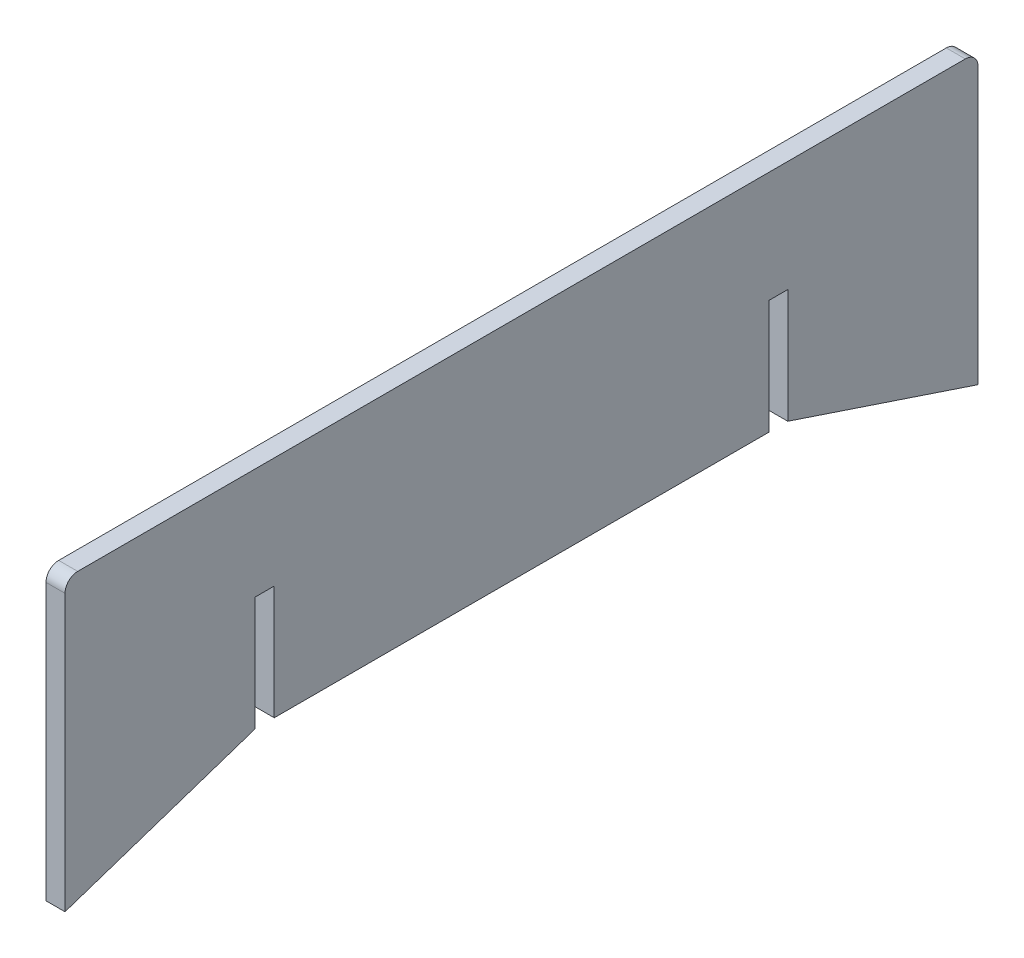
SolidWorks part; units mm, degrees
ref_plane "Front Plane" through (0, 0, 0) normal (0, 0, 1) x (1, 0, 0)
ref_plane "Top Plane" through (0, 0, 0) normal (0, 1, 0) x (1, 0, 0)
ref_plane "Right Plane" through (0, 0, 0) normal (1, 0, 0) x (0, 0, -1)
sketch "Sketch1" plane through (0, 0, 0) normal (1, 0, 0) x (0, 0, -1)
  line L1 (-72, -17.75) -> (72, -17.75)
  line L2 (-72, -17.75) -> (-72, 17.75)
  line L3 (-72, 17.75) -> (72, 17.75)
  line L4 (72, -17.75) -> (72, 17.75)
  line L5 (-72, -17.75) -> (72, 17.75) construction
  line L6 (-72, 17.75) -> (72, -17.75) construction
  point P0 (0, 0)
  dimension "D1" = 35.5
  dimension "D2" = 144
extrude "Boss-Extrude1" add sketch "Sketch1" along normal blind 3
fillet "Fillet1" radius 2 2 edges at (1.5, 17.75, -72) (1.5, 17.75, 72)
sketch "Sketch2" plane through (3, 0, 0) normal (1, 0, 0) x (0, 0, -1)
  line L0 (-72, -17.75) -> (72, -17.75) construction
  line L1 (-42, -17.75) -> (-39, -17.75)
  line L2 (-42, -17.75) -> (-42, 0.25)
  line L3 (-42, 0.25) -> (-39, 0.25)
  line L4 (-39, -17.75) -> (-39, 0.25)
  line L5 (-72, 15.75) -> (-72, -17.75) construction
  line L6 (0, 0) -> (0, -9.6726) construction
  line L7 (42, 0.25) -> (39, 0.25)
  line L8 (39, -17.75) -> (39, 0.25)
  line L9 (42, -17.75) -> (39, -17.75)
  line L10 (42, -17.75) -> (42, 0.25)
  dimension "D1" = 3
  dimension "D2" = 18
  dimension "D3" = 30
extrude "Cut-Extrude1" cut sketch "Sketch2" against normal blind 3
sketch "Sketch3" plane through (3, 0, 0) normal (1, 0, 0) x (0, 0, -1)
  line L0 (-72, -17.75) -> (-72, -27.75)
  line L1 (-72, -27.75) -> (-42, -17.75)
  line L2 (-72, -17.75) -> (-42, -17.75)
  dimension "D1" = 10
extrude "Boss-Extrude2" add sketch "Sketch3" against normal blind 3
mirror "Mirror1" about plane through (0, 0, 0) normal (0, 0, 1) of "Boss-Extrude2"
